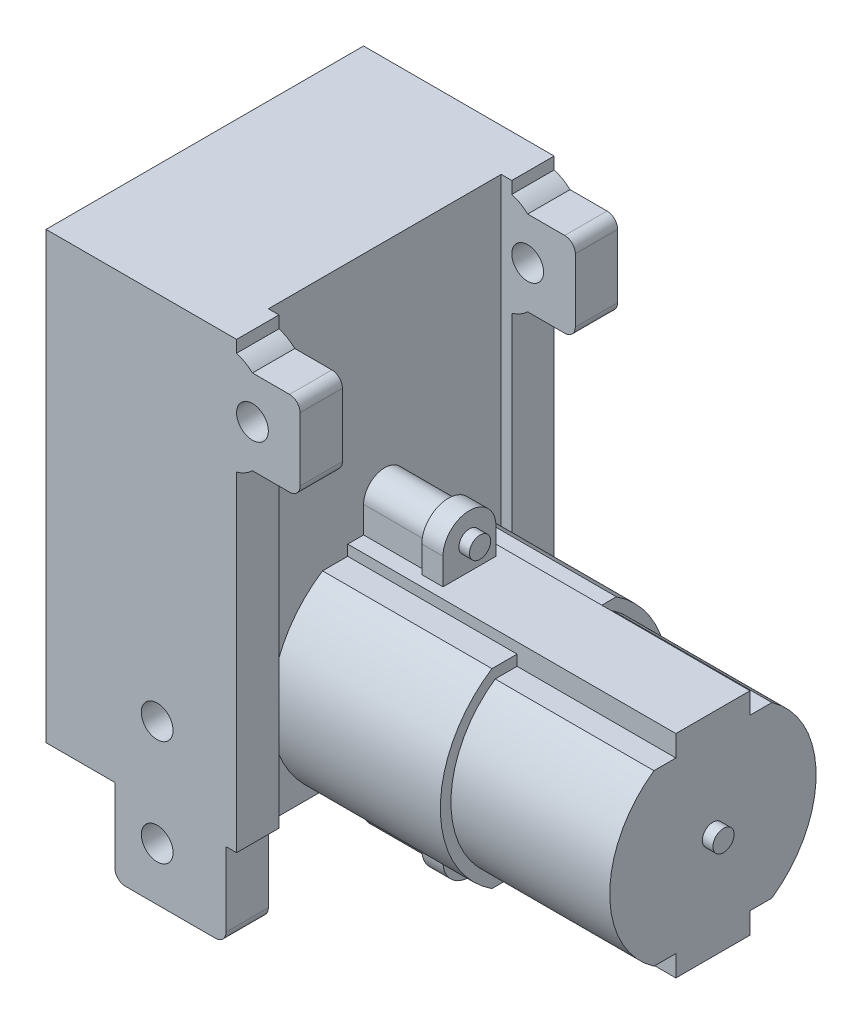
SolidWorks part; units mm, degrees
ref_plane "Plan de face" through (0, 0, 0) normal (0, 0, 1) x (1, 0, 0)
ref_plane "Plan de dessus" through (0, 0, 0) normal (0, 1, 0) x (1, 0, 0)
ref_plane "Plan de droite" through (0, 0, 0) normal (1, 0, 0) x (0, 0, -1)
sketch "Esquisse2" plane through (0, 0, 0) normal (0, 1, 0) x (1, 0, 0)
  line L0 (0, 0) -> (-73.9359, 0) construction
  line L1 (-22.1972, 11) -> (-39.1972, 11)
  line L2 (-22.1972, 11) -> (-22.1972, -11)
  line L3 (-22.1972, -11) -> (-39.1972, -11)
  line L4 (-39.1972, 11) -> (-39.1972, -11)
  line L5 (-22.1972, 11) -> (-39.1972, -11) construction
  line L6 (-22.1972, -11) -> (-39.1972, 11) construction
  point P0 (-30.6972, 0)
  dimension "D1" = 22
  dimension "D2" = 17
extrude "Base" add sketch "Esquisse2" against normal blind 42
sketch "Esquisse3" plane through (-39.1972, 0, 0) normal (-1, 0, 0) x (0, 0, 1)
  line L0 (-11, 0) -> (11, -42) construction
  line L1 (-8.3832, -21) -> (8.1655, -21) construction
  line L2 (0, -5.0229) -> (0, -37.1949) construction
  circle A0 centre (0, -8.7246) radius 6
  circle A1 centre (0, -33.2754) radius 6
  point P4 (0, -21)
  dimension "D1" = 12
extrude "VIDE CERCLE" cut sketch "Esquisse3" against normal blind 2
sketch "Esquisse4" plane through (-37.1972, 0, 0) normal (-1, 0, 0) x (0, 0, 1)
  line L1 (1.7854, -6.9746) -> (-1.7854, -6.9746)
  line L3 (1.7854, -10.4746) -> (-1.7854, -10.4746)
  line L5 (1.7854, -6.9746) -> (-1.7854, -10.4746) construction
  line L6 (1.7854, -10.4746) -> (-1.7854, -6.9746) construction
  arc A0 (-1.7854, -6.9746) -> (-1.7854, -10.4746) centre (0, -8.7246) ccw
  arc A1 (1.7854, -10.4746) -> (1.7854, -6.9746) centre (0, -8.7246) ccw
  circle A2 centre (0, -8.7246) radius 1
  dimension "D1" = 5
  dimension "D3" = 2
  dimension "D2" = 3.5
extrude "AXE ROUE" add sketch "Esquisse4" along normal blind 8
sketch "Esquisse6" plane through (0, 0, 11) normal (0, 0, 1) x (1, 0, 0)
  line L0 (-36.9634, -6) -> (-14.5899, -6) construction
  line L1 (-39.1972, 0) -> (-22.1972, 0) construction
  line L2 (-22.1972, -42) -> (-22.1972, 0) construction
  line L3 (-19.6972, -6) -> (-19.6972, -1) construction
  line L4 (-39.1972, 0) -> (-22.1972, -42) construction
  line L5 (-19.6972, -2) -> (-16.1972, -2)
  line L6 (-22.1972, 0) -> (-39.1972, 0)
  line L8 (-32.6972, -42) -> (-39.1972, -42)
  line L9 (-39.1972, 0) -> (-39.1972, -42)
  line L10 (-22.1972, 0) -> (-39.1972, -42) construction
  line L11 (-22.1972, -42) -> (-39.1972, 0) construction
  line L12 (-15.1972, -3) -> (-15.1972, -9)
  line L13 (-19.6972, -10) -> (-16.1972, -10)
  line L14 (-32.6972, -42) -> (-32.6972, -49)
  line L15 (-22.1972, -42) -> (-22.1972, -49)
  line L16 (-23.1972, -50) -> (-31.6972, -50)
  line L17 (-22.1972, -42) -> (-21.1972, -42)
  line L18 (-21.1972, -42) -> (-21.1972, -10.8593)
  line L19 (-21.1972, -10.8593) -> (-21.1972, 1.2149) construction
  line L20 (-22.1972, 0) -> (-21.1972, 0)
  line L21 (-21.1972, 0) -> (-21.1972, -1.1407)
  circle A0 centre (-19.6972, -6) radius 1.5
  arc A1 (-19.6972, -2) -> (-21.1972, -1.1407) centre (-22.1972, -4.625) ccw
  arc A2 (-15.1972, -3) -> (-16.1972, -2) centre (-16.1972, -3) ccw
  arc A3 (-15.1972, -9) -> (-16.1972, -10) centre (-16.1972, -9) cw
  arc A4 (-19.6972, -10) -> (-21.1972, -10.8593) centre (-22.1972, -7.375) cw
  circle A5 centre (-28.6972, -35) radius 1.5
  circle A6 centre (-28.6972, -45) radius 1.5
  arc A7 (-22.1972, -49) -> (-23.1972, -50) centre (-23.1972, -49) cw
  arc A8 (-31.6972, -50) -> (-32.6972, -49) centre (-31.6972, -49) cw
  point P4 (-15.1972, -6)
  point P7 (-19.6972, -6)
  point P8 (-22.1972, -1)
  point P9 (-22.1972, -11)
  point P12 (-19.6972, -2)
  point P15 (-22.1972, -1)
  point P22 (-30.6972, -21)
  point P33 (-15.1972, -6)
  point P36 (-28.6972, -35)
  point P39 (-28.6972, -50)
  point P40 (-28.6972, -45)
  point P41 (-32.6972, -42)
  dimension "D6" = 3
  dimension "D8" = 1
  dimension "D11" = 3
  dimension "D15" = 3
  dimension "D16" = 1
  dimension "D1" = 6
  dimension "D2" = 7
  dimension "D3" = 4.5
  dimension "D4" = 5
  dimension "D5" = 5
  dimension "D7" = 4
  dimension "D9" = 10.5
  dimension "D10" = 35
  dimension "D12" = 15
  dimension "D13" = 10
  dimension "D14" = 6.5
  dimension "D17" = 1
extrude "COTE" add sketch "Esquisse6" along normal blind 4
mirror "SYM COTE" about plane through (0, 0, 0) normal (0, 0, 1) of "COTE"
sketch "Esquisse7" plane through (0, 0, -11) normal (0, 0, 1) x (1, 0, 0)
  line L1 (-32.6972, -42) -> (-22.1972, -42)
  line L2 (-32.6972, -42) -> (-32.6972, -50)
  line L3 (-32.6972, -50) -> (-22.1972, -50)
  line L4 (-22.1972, -42) -> (-22.1972, -50)
extrude "AJUSTE COTE" cut sketch "Esquisse7" against normal blind 4
sketch "Esquisse8" plane through (-22.1972, 0, 0) normal (1, 0, 0) x (0, 0, -1)
  line L0 (0, 0) -> (0, -46.0294) construction
  line L1 (-11, -42) -> (11, -42) construction
  line L2 (-5.879, -42) -> (5.879, -42)
  line L3 (-4.1088, -33) -> (4.3629, -33) construction
  line L4 (-5.879, -24) -> (5.879, -24)
  line L5 (3.5, -23) -> (-3.5, -23)
  line L6 (-5.879, -42) -> (5.879, -24) construction
  line L7 (-5.879, -24) -> (5.879, -42) construction
  line L8 (3.5, -23) -> (3.5, -24)
  line L9 (-3.5, -43) -> (-3.5, -42)
  line L10 (-3.5, -23) -> (-3.5, -24)
  line L11 (3.5, -23) -> (-2.6947, -24.7699) construction
  line L12 (4.5862, -25.3103) -> (-3.5, -23) construction
  line L13 (3.5, -43) -> (3.5, -42)
  line L14 (3.5, -43) -> (-3.5, -43)
  line L15 (0, -23) -> (0, -24) construction
  arc A0 (-5.879, -24) -> (-5.879, -42) centre (0, -33) ccw
  arc A1 (5.879, -42) -> (5.879, -24) centre (0, -33) ccw
  point P4 (0, -24)
  point P23 (0, -23)
  line M1 (-11, -42) -> (11, -42)
  dimension "D1" = 21.5
  dimension "D2" = 18
  dimension "D3" = 1
  dimension "D4" = 7
extrude "BLOC MOTEUR" add sketch "Esquisse8" along normal blind 31 contours A1 L4 A0 L2 M1 | L14 L13 L2 L9 | L5 L10 L4 L8
sketch "Esquisse10" plane through (8.8028, 0, 0) normal (1, 0, 0) x (0, 0, -1)
  line L0 (-6.7398, -33) -> (6.3509, -33) construction
  line L1 (-5.879, -24) -> (-3.5, -24)
  line L5 (3.5, -24) -> (5.879, -24)
  line L6 (-5.879, -42) -> (-3.5, -42)
  line L12 (3.5, -42) -> (5.879, -42)
  line L13 (-5.879, -24) -> (-5.879, -42) construction
  line L14 (-3.5, -24) -> (-3.5, -42) construction
  line L15 (3.5, -24) -> (3.5, -42) construction
  line L16 (5.879, -24) -> (5.879, -42) construction
  line L17 (-3.5, -25) -> (-5.5734, -25)
  line L18 (3.5, -25) -> (5.5734, -25)
  line L19 (-3.5, -24) -> (-3.5, -25)
  line L20 (3.5, -25) -> (3.5, -24)
  line L21 (3.5, -41) -> (3.5, -42)
  line L22 (-3.5, -42) -> (-3.5, -41)
  line L23 (3.5, -41) -> (5.5734, -41)
  line L24 (-3.5, -41) -> (-5.5734, -41)
  arc A0 (-5.879, -24) -> (-5.879, -42) centre (0, -33) ccw
  arc A1 (5.879, -42) -> (5.879, -24) centre (0, -33) ccw
  arc A2 (-5.5734, -25) -> (-5.5734, -41) centre (0, -33) ccw
  arc A4 (5.5734, -41) -> (5.5734, -25) centre (0, -33) ccw
  dimension "D1" = 1
  dimension "D2" = 1
  dimension "D3" = 1
extrude "VODE MOTEUR" cut sketch "Esquisse10" against normal blind 15
sketch "Esquisse11" plane through (8.8028, 0, 0) normal (1, 0, 0) x (0, 0, -1)
  circle A0 centre (0, -33) radius 1
  point P0 (0, -33)
  dimension "D1" = 2
extrude "SORTIE AXE MOTEUR" add sketch "Esquisse11" along normal blind 1
sketch "Esquisse12" plane through (-22.1972, 0, 0) normal (1, 0, 0) x (0, 0, -1)
  line L0 (3.5, -23) -> (-3.5, -23) construction
  line L1 (-2, -20.5) -> (-2, -23)
  line L2 (2, -20.5) -> (2, -23)
  line L3 (0, -33) -> (-12.0538, -33) construction
  line L4 (2, -45.5) -> (2, -43)
  line L5 (-2, -45.5) -> (-2, -43)
  line L6 (-2, -23) -> (2, -23)
  line L7 (-2, -43) -> (2, -43)
  arc A0 (2, -20.5) -> (-2, -20.5) centre (0, -20.5) ccw
  arc A1 (2, -45.5) -> (-2, -45.5) centre (0, -45.5) cw
  dimension "D1" = 4
  dimension "D2" = 2.5
extrude "VIS MOTEUR 1" add sketch "Esquisse12" along normal blind 6
sketch "Esquisse14" plane through (-16.1972, 0, 0) normal (1, 0, 0) x (0, 0, -1)
  line L0 (-2, -20.5) -> (2, -20.5) construction
  line L1 (-2.5, -20.5) -> (-2.5, -23)
  line L2 (3.5, -23) -> (-3.5, -23) construction
  line L3 (-2.5, -23) -> (2.5, -23)
  line L4 (3.5, -23) -> (2, -23) construction
  line L5 (2.5, -23) -> (2.5, -20.5)
  line L6 (0, -33) -> (-4.8601, -33) construction
  line L7 (-2.5, -43) -> (2.5, -43)
  line L8 (-2.5, -45.5) -> (-2.5, -43)
  line L9 (2.5, -43) -> (2.5, -45.5)
  arc A0 (2.5, -20.5) -> (-2.5, -20.5) centre (0, -20.5) ccw
  arc A1 (2, -20.5) -> (-2, -20.5) centre (0, -20.5) ccw construction
  arc A2 (2.5, -45.5) -> (-2.5, -45.5) centre (0, -45.5) cw
  dimension "D1" = 0.5
extrude "VIS MOTEUR 2" add sketch "Esquisse14" along normal blind 2
sketch "Esquisse15" plane through (-14.1972, 0, 0) normal (1, 0, 0) x (0, 0, -1)
  line L0 (-2.5, -20.5) -> (2.5, -20.5) construction
  line L1 (0, -33) -> (-3.5484, -33) construction
  circle A0 centre (0, -20.5) radius 1
  circle A1 centre (0, -45.5) radius 1
  dimension "D1" = 2
extrude "VIS MOTEUR 3" add sketch "Esquisse15" along normal blind 1
